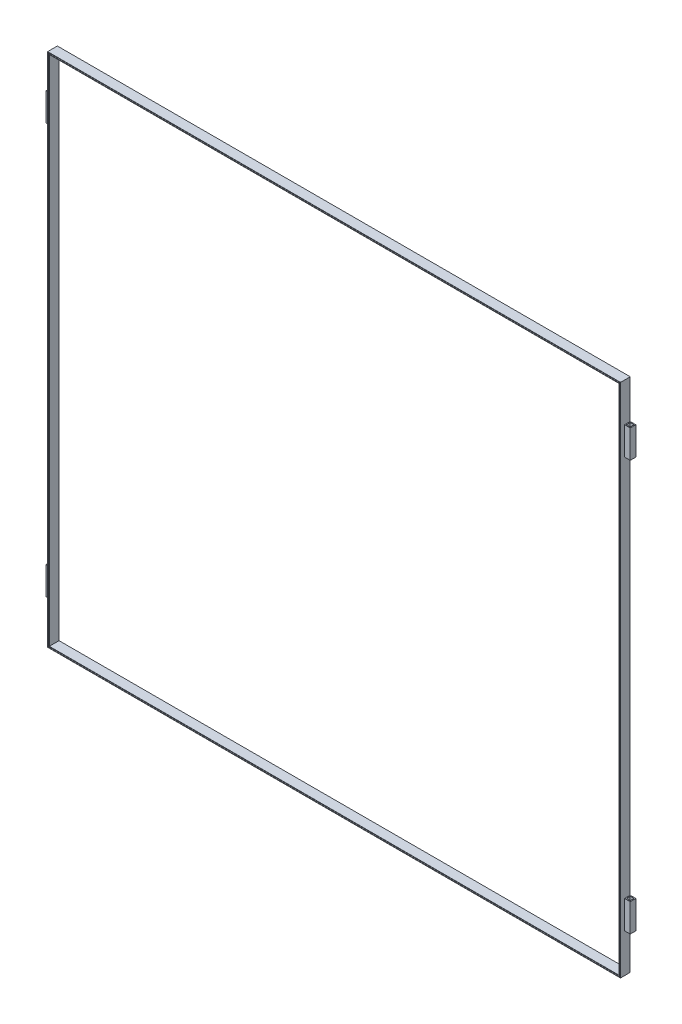
SolidWorks part; units mm, degrees
ref_plane "Front Plane" through (0, 0, 0) normal (0, 0, 1) x (1, 0, 0)
ref_plane "Top Plane" through (0, 0, 0) normal (0, 1, 0) x (1, 0, 0)
ref_plane "Right Plane" through (0, 0, 0) normal (1, 0, 0) x (0, 0, -1)
sketch "Sketch1" plane through (0, 0, 0) normal (0, 0, 1) x (1, 0, 0)
  line L0 (-1529, 1376.6) -> (-1529, -1376.6)
  line L1 (-1524, 1371.6) -> (1524, 1371.6)
  line L2 (-1524, 1371.6) -> (-1524, -1371.6)
  line L3 (-1524, -1371.6) -> (1524, -1371.6)
  line L4 (1524, 1371.6) -> (1524, -1371.6)
  line L5 (-1524, 1371.6) -> (1524, -1371.6) construction
  line L6 (-1524, -1371.6) -> (1524, 1371.6) construction
  line L7 (-1529, -1376.6) -> (1529, -1376.6)
  line L8 (1529, 1376.6) -> (1529, -1376.6)
  line L9 (-1529, 1376.6) -> (1529, 1376.6)
  point P0 (0, 0)
  dimension "D1" = 3048
  dimension "D2" = 2743.2
  dimension "D3" = 5
extrude "Boss-Extrude1" add sketch "Sketch1" along normal blind 50
shell "Shell4" thickness 2
sketch "Sketch2" plane through (0, 0, 0) normal (0, 0, 1) x (1, 0, 0)
  line L1 (-1524, 1371.6) -> (1524, 1371.6)
  line L2 (-1524, 1371.6) -> (-1524, -1371.6)
  line L3 (-1524, -1371.6) -> (1524, -1371.6)
  line L4 (1524, 1371.6) -> (1524, -1371.6)
  line L5 (-1524, 1371.6) -> (1524, -1371.6) construction
  line L6 (-1524, -1371.6) -> (1524, 1371.6) construction
  line L7 (-1529, 1376.6) -> (1529, 1376.6)
  line L8 (-1529, 1376.6) -> (-1529, -1376.6)
  line L9 (-1529, -1376.6) -> (1529, -1376.6)
  line L10 (1529, 1376.6) -> (1529, -1376.6)
  line L11 (-1529, 1376.6) -> (1529, -1376.6) construction
  line L12 (-1529, -1376.6) -> (1529, 1376.6) construction
  point P0 (0, 0)
  point P5 (0, 0)
extrude "Cut-Extrude5" cut sketch "Sketch2" along normal mid plane 10
sketch "Sketch3" plane through (1531, 0, 0) normal (1, 0, 0) x (0, 0, -1)
  line L0 (2, -1378.6) -> (2, 1378.6) construction
  line L1 (2, 1171.4) -> (-28, 1171.4)
  line L2 (2, 1171.4) -> (2, 1021.4)
  line L3 (2, 1021.4) -> (-28, 1021.4)
  line L4 (-28, 1171.4) -> (-28, 1021.4)
  line L5 (-50, -1378.6) -> (2, -1378.6) construction
  dimension "D1" = 150
  dimension "D2" = 30
  dimension "D3" = 2400
extrude "Boss-Extrude2" add sketch "Sketch3" along normal blind 30
sketch "Sketch4" plane through (0, 1171.4, 0) normal (0, 1, 0) x (1, 0, 0)
  line L2 (1561, -28) -> (1531, -28) construction
  line L3 (1536, -3) -> (1556, -3)
  line L4 (1536, -3) -> (1536, -23)
  line L5 (1536, -23) -> (1556, -23)
  line L6 (1556, -3) -> (1556, -23)
  line L7 (1536, -3) -> (1556, -23) construction
  line L8 (1536, -23) -> (1556, -3) construction
  line L9 (1561, 2) -> (1561, -28) construction
  point P0 (1546, -13)
  dimension "D1" = 5
  dimension "D3" = 20
  dimension "D2" = 5
  dimension "D4" = 20
extrude "Cut-Extrude6" cut sketch "Sketch4" against normal blind 100
mirror "Mirror1" about plane through (0, 0, 0) normal (0, 1, 0) of "Boss-Extrude2"
sketch "Sketch5" plane through (0, -1021.4, 0) normal (0, 1, 0) x (1, 0, 0)
  line L6 (1556, -3) -> (1536, -3)
  line L7 (1556, -23) -> (1556, -3)
  line L8 (1536, -23) -> (1556, -23)
  line L9 (1536, -3) -> (1536, -23)
  line L10 (1556, -3) -> (1536, -3)
  line L11 (1556, -23) -> (1556, -3)
  line L12 (1536, -23) -> (1556, -23)
  line L13 (1536, -3) -> (1536, -23)
  dimension "D1" = 0
extrude "Cut-Extrude7" cut sketch "Sketch5" against normal blind 100
mirror "Mirror2" about plane through (0, 0, 0) normal (1, 0, 0) of "Mirror1", "Boss-Extrude2"
mirror "Mirror3" about plane through (0, 0, 0) normal (1, 0, 0) of "Cut-Extrude7", "Cut-Extrude6"
sketch "Sketch6" plane through (0, 1071.4, 0) normal (0, 1, 0) x (1, 0, 0)
  line L0 (1536, -23) -> (1556, -23) construction
  line L1 (1556, -23) -> (1556, -3) construction
  circle A0 centre (1546, -13) radius 5
  point P6 (1556, -13)
  dimension "D1" = 10
  dimension "D2" = 10
  dimension "D3" = 10
extrude "Cut-Extrude8" cut sketch "Sketch6" against normal blind 2490
sketch "Sketch7" plane through (1524, 0, 0) normal (1, 0, 0) x (0, 0, -1)
  line L0 (-50, -1378.6) -> (-50, 1378.6) construction
  line L1 (-50, 1371.6) -> (2, 1371.6)
  line L2 (-50, 1371.6) -> (-50, 1378.6)
  line L3 (-50, 1378.6) -> (2, 1378.6)
  line L4 (2, 1371.6) -> (2, 1378.6)
  point P7 (2, 1371.6)
  dimension "D1" = 52
extrude "Boss-Extrude3" add sketch "Sketch7" against normal blind 2
mirror "Mirror4" about plane through (0, 0, 0) normal (0, 1, 0) of "Boss-Extrude3"
mirror "Mirror5" about plane through (0, 0, 0) normal (1, 0, 0) of "Boss-Extrude3", "Mirror4"
